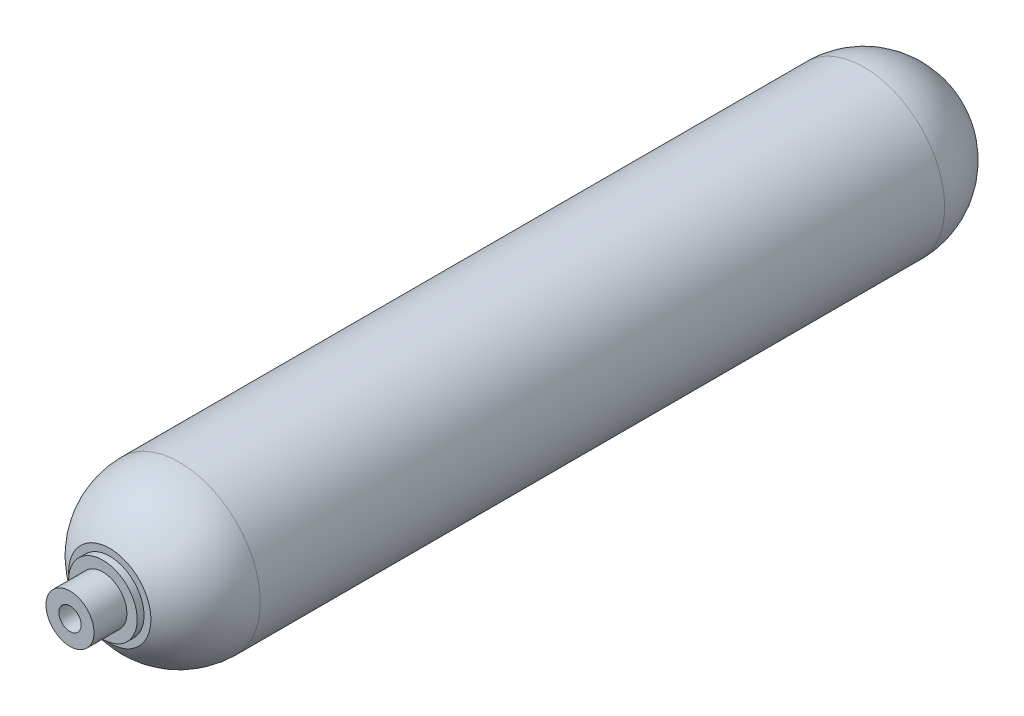
SolidWorks part; units mm, degrees
material "Std Carbon Fiber Fabric"
ref_plane "Front Plane" through (0, 0, 0) normal (0, 0, 1) x (1, 0, 0)
ref_plane "Top Plane" through (0, 0, 0) normal (0, 1, 0) x (1, 0, 0)
ref_plane "Right Plane" through (0, 0, 0) normal (1, 0, 0) x (0, 0, -1)
sketch "Sketch1" plane through (0, 0, 0) normal (0, 1, 0) x (1, 0, 0)
  line L0 (0, 0) -> (31.75, 0)
  line L1 (31.75, 0) -> (31.75, 6.35)
  line L2 (31.75, 6.35) -> (38.1, 6.35)
  line L3 (0, 704.85) -> (0, -24.8775) construction
  line L4 (74.93, 704.85) -> (74.93, 70.8705)
  line L5 (0, 0) -> (0, 5.08)
  line L6 (0, 5.08) -> (26.67, 5.08)
  line L7 (26.67, 5.08) -> (26.67, 11.43)
  line L8 (26.67, 11.43) -> (40.1946, 11.43)
  line L9 (71.755, 70.8705) -> (71.755, 704.85)
  line L10 (0, 776.605) -> (0, 779.78)
  arc A0 (0, 779.78) -> (74.93, 704.85) centre (0, 704.85) cw
  arc A1 (74.93, 70.8705) -> (38.1, 6.35) centre (0, 70.8705) cw
  arc A2 (71.755, 70.8705) -> (40.1946, 11.43) centre (0, 70.8705) cw
  arc A3 (0, 776.605) -> (71.755, 704.85) centre (0, 704.85) cw
  dimension "D1" = 74.93
  dimension "D2" = 5.08
  dimension "D4" = 31.75
  dimension "D5" = 6.35
  dimension "D6" = 6.35
  dimension "D7" = 5.08
  dimension "D8" = 5.08
  dimension "D9" = 3.175
  dimension "D10" = 779.78
  dimension "D11" = 3.175
revolve "Revolve1" add sketch "Sketch1" angle 360 about L3
sketch "Sketch4" plane through (0, 0, 0) normal (0, 0, 1) x (1, 0, 0)
  circle A0 centre (0, 0) radius 22.225
  dimension "D1" = 44.45
extrude "Boss-Extrude1" add sketch "Sketch4" along normal blind 30.48
hole_wizard "7/8-14 UNF Fitting" positions "Sketch3" profile "Sketch2" tap size "7/8-14" standard "ANSI Inch"
sketch "Sketch3" plane through (-8.5906, 4.9681, 30.48) normal (0, 0, 1) x (1, 0, 0)
  point P0 (8.5906, -4.9681)
sketch "Sketch2" plane through (0, 0, 30.48) normal (1, 0, 0) x (0, -1, 0)
  line L0 (0, 0) -> (0, 55.9841)
  line L1 (0, 55.9841) -> (10.3187, 49.784)
  line L2 (10.3187, 49.784) -> (10.3187, 0)
  line L5 (10.3187, 0) -> (0, 0)
  line L10 (0, 55.9841) -> (-10.3188, 49.784) construction
  line L11 (0, -6.35) -> (0, 107.95) construction
  dimension "Tap Drill Dia." = 20.6375
  dimension "Tap Drill Depth" = 49.784
  dimension "Drill Angle" = 118
cosmetic thread "Hole Thread2" parameters "D1"=5.08, "D2"=22.225
